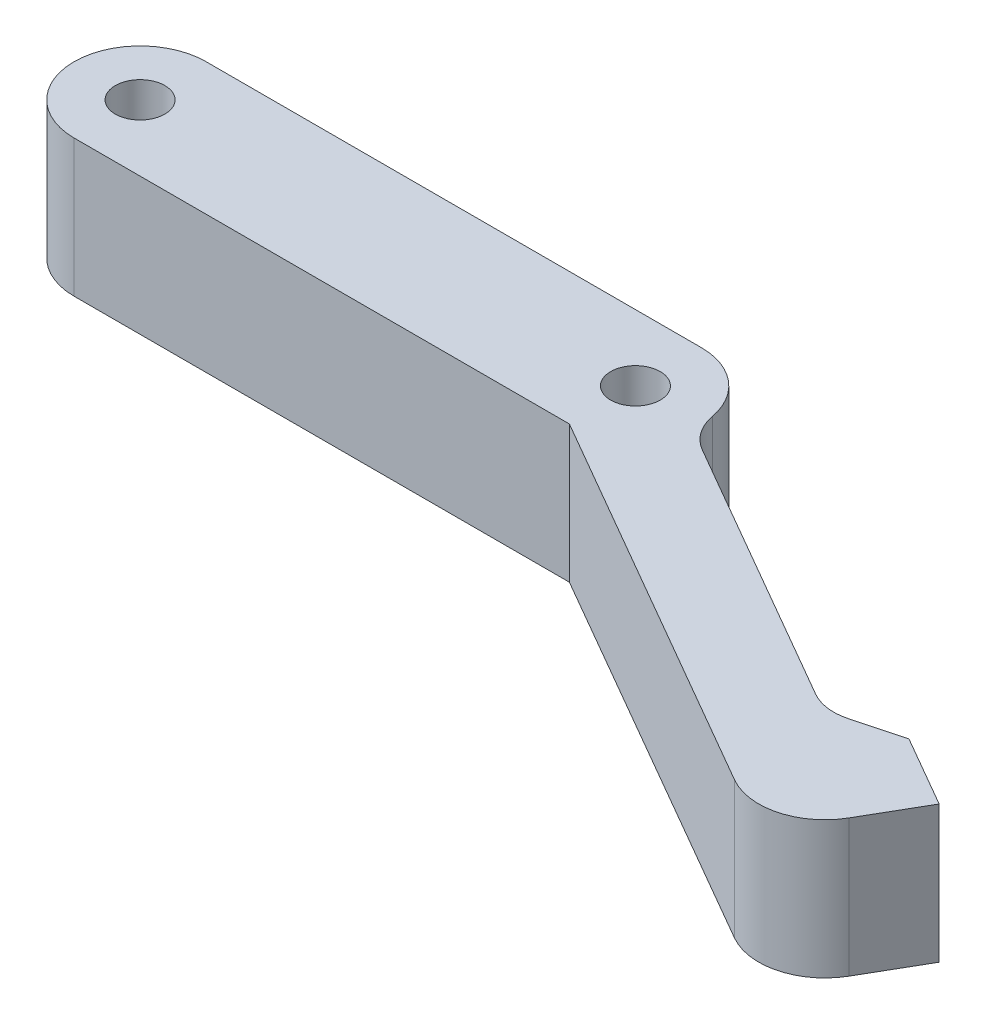
SolidWorks part; units mm, degrees
ref_plane "Front Plane" through (0, 0, 0) normal (0, 0, 1) x (1, 0, 0)
ref_plane "Top Plane" through (0, 0, 0) normal (0, 1, 0) x (1, 0, 0)
ref_plane "Right Plane" through (0, 0, 0) normal (1, 0, 0) x (0, 0, -1)
sketch "Sketch1" plane through (0, 0, 0) normal (0, 1, 0) x (1, 0, 0)
  line L0 (0, 0) -> (30, 0) construction
  line L1 (0, 4) -> (30, 4)
  line L2 (33.9665, -0.5166) -> (52.6992, -11.3319)
  line L3 (30, -4) -> (30, 4) construction
  line L4 (52.6992, -11.3319) -> (56.7972, -10.2338)
  line L5 (0, -4) -> (30, -4)
  line L6 (56.7972, -10.2338) -> (61.1274, -12.7338)
  line L7 (59.1274, -16.1979) -> (61.1274, -12.7338)
  line L8 (53.6633, -17.662) -> (30, -4)
  circle A0 centre (0, 0) radius 1.5
  circle A1 centre (30, 0) radius 1.5
  arc A2 (0, 4) -> (0, -4) centre (0, 0) ccw
  arc A6 (53.6633, -17.662) -> (59.1274, -16.1979) centre (55.6633, -14.1979) ccw
  arc A7 (33.9665, -0.5166) -> (30, 4) centre (30, 0) ccw
  point P5 (56.8307, -12.5599)
  point P11 (54.9312, -11.4658)
  dimension "D2" = 3
  dimension "D3" = 8
  dimension "D1" = 30
  dimension "D4" = 210
  dimension "D6" = 135
  dimension "D7" = 5
  dimension "D8" = 5
  dimension "D9" = 4
extrude "Boss-Extrude1" add sketch "Sketch1" along normal blind 8.3
fillet "Fillet1" radius 3 2 edges at (52.6992, 4.15, 11.3319) (33.9665, 4.15, 0.5166)
